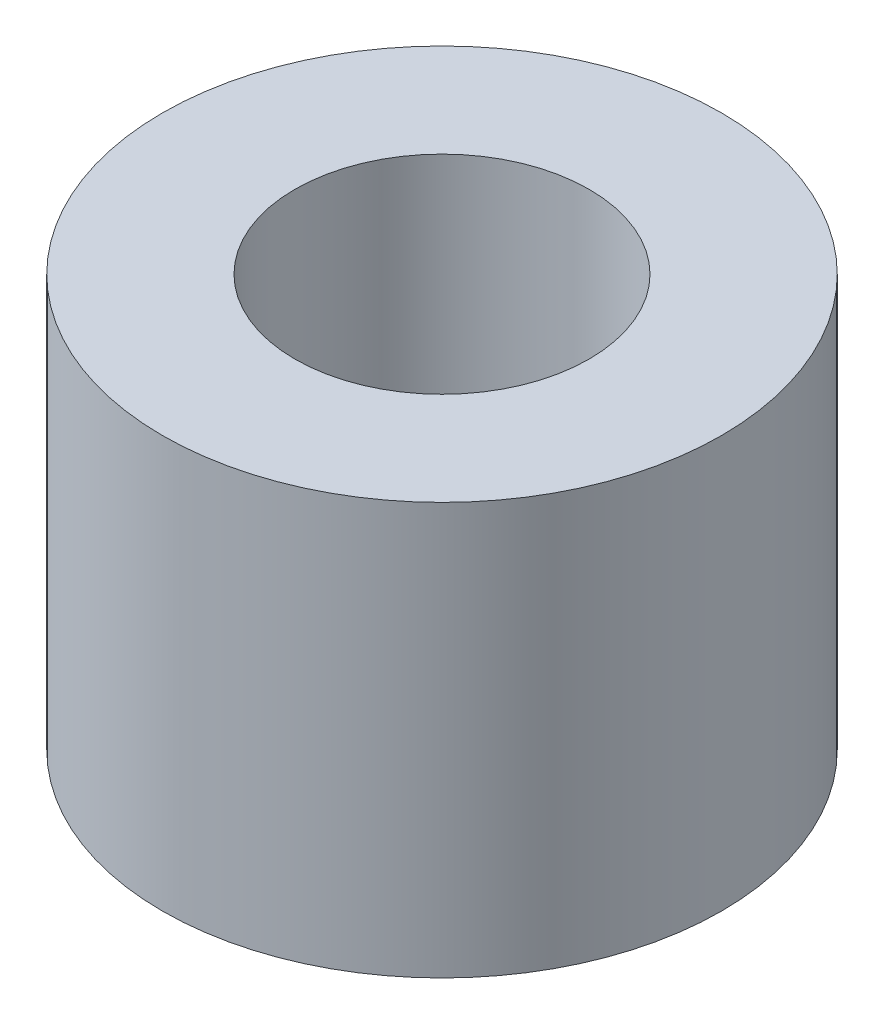
SolidWorks part; units mm, degrees
material "Polyethylene Cross-Linked"
ref_plane "Front Plane" through (0, 0, 0) normal (0, 0, 1) x (1, 0, 0)
ref_plane "Top Plane" through (0, 0, 0) normal (0, 1, 0) x (1, 0, 0)
ref_plane "Right Plane" through (0, 0, 0) normal (1, 0, 0) x (0, 0, -1)
sketch "Sketch1" plane through (0, 0, 0) normal (0, 1, 0) x (1, 0, 0)
  circle A0 centre (0, 0) radius 9.5
  circle A1 centre (0, 0) radius 5
  dimension "D1" = 10
  dimension "D2" = 19
extrude "Boss-Extrude1" add sketch "Sketch1" along normal blind 14
